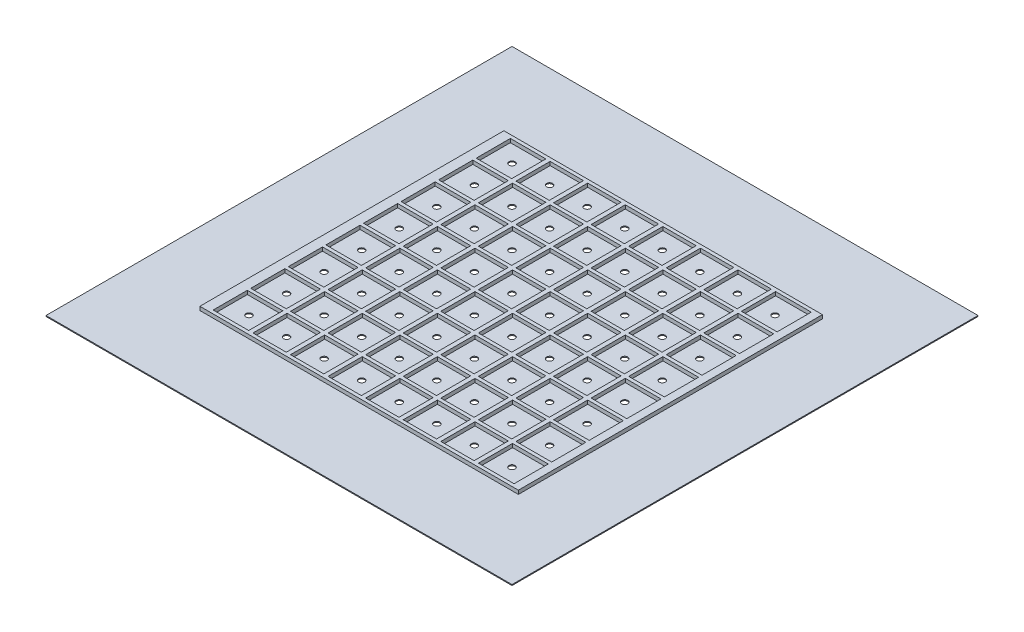
SolidWorks part; units mm, degrees
ref_plane "Front Plane" through (0, 0, 0) normal (0, 0, 1) x (1, 0, 0)
ref_plane "Top Plane" through (0, 0, 0) normal (0, 1, 0) x (1, 0, 0)
ref_plane "Right Plane" through (0, 0, 0) normal (1, 0, 0) x (0, 0, -1)
sketch "Sketch1" plane through (0, 0, 0) normal (0, 1, 0) x (1, 0, 0)
  line L1 (-315, -315) -> (315, -315)
  line L2 (-315, -315) -> (-315, 315)
  line L3 (-315, 315) -> (315, 315)
  line L4 (315, -315) -> (315, 315)
  line L5 (0, 315) -> (0, -315) construction
  line L6 (-315, 0) -> (315, 0) construction
  point P0 (0, 0)
  dimension "D1" = 630
  dimension "D2" = 630
extrude "Boss-Extrude1" add sketch "Sketch1" along normal blind 1.2426
sketch "Sketch2" plane through (0, 1.2426, 0) normal (0, 1, 0) x (1, 0, 0)
  line L1 (203.4, -203.4) -> (-203.4, -203.4)
  line L2 (203.4, -203.4) -> (203.4, 203.4)
  line L3 (203.4, 203.4) -> (-203.4, 203.4)
  line L4 (-203.4, -203.4) -> (-203.4, 203.4)
  line L5 (0, 203.4) -> (0, -203.4) construction
  line L6 (203.4, 0) -> (-203.4, 0) construction
  point P0 (0, 0)
sketch "Sketch3" plane through (0, 1.2426, 0) normal (0, 1, 0) x (1, 0, 0)
  line L1 (-203.4, 203.4) -> (-152.6, 203.4)
  line L2 (-203.4, 203.4) -> (-203.4, 152.6)
  line L3 (-203.4, 152.6) -> (-152.6, 152.6)
  line L4 (-152.6, 203.4) -> (-152.6, 152.6)
  point P5 (-178, 178)
  dimension "D1" = 50.8
  dimension "D2" = 50.8
sketch "Sketch6" plane through (0, 1.2426, 0) normal (0, 1, 0) x (1, 0, 0)
  circle A0 centre (-178, 178) radius 4.1
  dimension "D1" = 8.2
extrude "Cut-Extrude1" cut sketch "Sketch6" against normal through all
pattern_linear "LPattern1" count 8 spacing 50.8 along (1, 0, 0) count 8 spacing 50.8 along (0, 0, 1) of "Cut-Extrude1"
sketch "Sketch7" plane through (0, 1.2426, 0) normal (0, 1, 0) x (1, 0, 0)
  line L0 (-203.3894, 150.385) -> (-203.3894, 154.985)
  line L1 (-203.3894, 150.385) -> (203.4078, 150.385)
  line L2 (-203.3894, 154.985) -> (203.4078, 154.985)
  line L3 (203.4078, 150.385) -> (203.4078, 154.985)
extrude "Boss-Extrude4" add sketch "Sketch7" along normal blind 5
pattern_linear "LPattern3" count 8 spacing 50.8 along (0, 0, 1) count 2 spacing 50.8 along (0, 0, -1) of "Boss-Extrude4"
sketch "Sketch9" plane through (0, 1.2426, 0) normal (0, 1, 0) x (1, 0, 0)
  line L1 (-203.3894, 205.785) -> (-216.7491, 205.785)
  line L2 (-203.3894, 205.785) -> (-203.3894, -205.215)
  line L3 (-203.3894, -205.215) -> (-216.7491, -205.215)
  line L4 (-216.7491, 205.785) -> (-216.7491, -205.215)
  line L5 (203.4078, 205.785) -> (213.8412, 205.785)
  line L6 (203.4078, 205.785) -> (203.4078, -205.215)
  line L7 (203.4078, -205.215) -> (213.8412, -205.215)
  line L8 (213.8412, 205.785) -> (213.8412, -205.215)
extrude "Boss-Extrude5" add sketch "Sketch9" along normal blind 5
sketch "Sketch10" plane through (0, 1.2426, 0) normal (0, 1, 0) x (1, 0, 0)
  line L0 (-203.3894, 201.185) -> (203.4078, 201.185) construction
  line L1 (-155.4014, 201.185) -> (-149.6235, 201.185)
  line L2 (-155.4014, 201.185) -> (-155.4014, 154.985)
  line L3 (-155.4014, 154.985) -> (-149.6235, 154.985)
  line L4 (-149.6235, 201.185) -> (-149.6235, 154.985)
  line L5 (203.4078, 154.985) -> (-203.3894, 154.985) construction
extrude "Boss-Extrude6" add sketch "Sketch10" along normal blind 5
pattern_linear "LPattern4" count 7 spacing 50.8 along (1, 0, 0) count 8 spacing 50.8 along (0, 0, 1) of "Boss-Extrude6"
